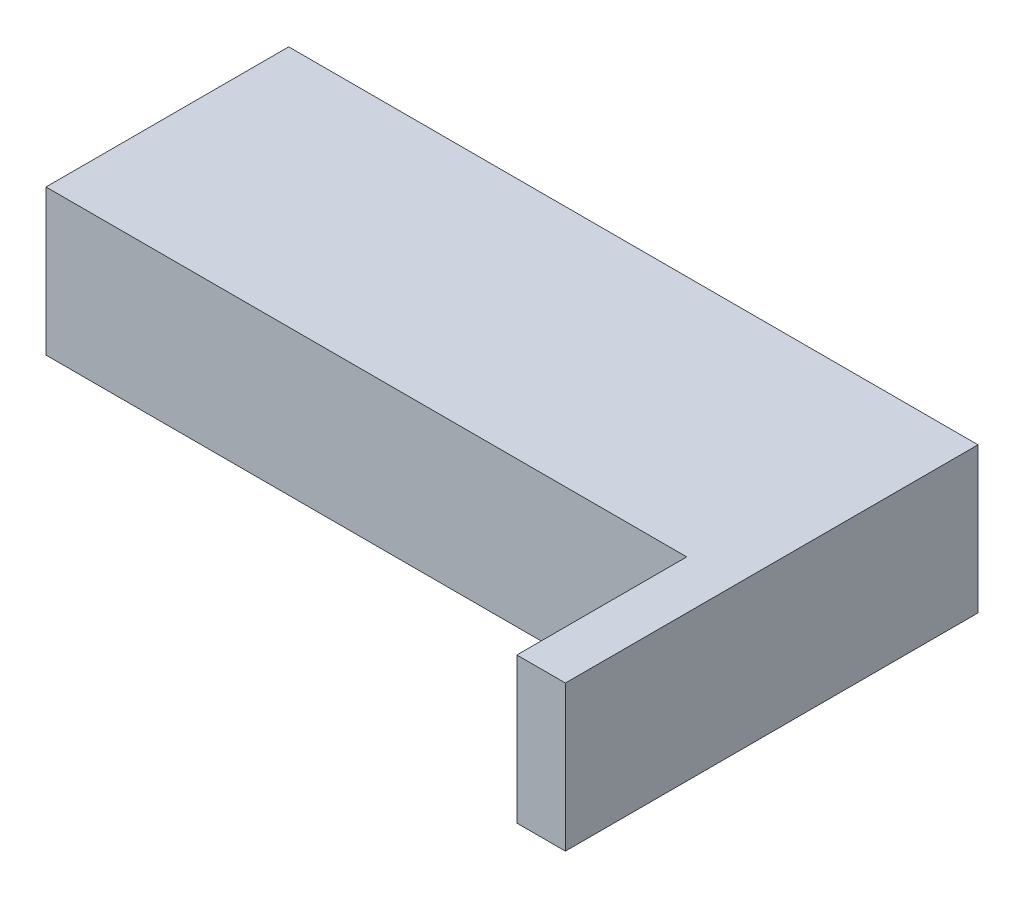
SolidWorks part; units mm, degrees
ref_plane "Front Plane" through (0, 0, 0) normal (0, 0, 1) x (1, 0, 0)
ref_plane "Top Plane" through (0, 0, 0) normal (0, 1, 0) x (1, 0, 0)
ref_plane "Right Plane" through (0, 0, 0) normal (1, 0, 0) x (0, 0, -1)
sketch "Sketch1" plane through (0, 0, 0) normal (0, 1, 0) x (1, 0, 0)
  line L1 (0, 0) -> (142, 0)
  line L2 (0, 0) -> (0, 50)
  line L3 (0, 50) -> (142, 50)
  line L4 (142, 0) -> (142, 50)
  dimension "D1" = 50
  dimension "D2" = 142
extrude "Boss-Extrude1" add sketch "Sketch1" along normal blind 30
sketch "Sketch2" plane through (0, 0, 0) normal (0, 0, 1) x (1, 0, 0)
  line L0 (0, 30) -> (142, 30) construction
  line L1 (132, 30) -> (142, 30)
  line L2 (132, 30) -> (132, 0)
  line L3 (132, 0) -> (142, 0)
  line L4 (142, 30) -> (142, 0)
  dimension "D1" = 10
extrude "Boss-Extrude2" add sketch "Sketch2" along normal blind 35
